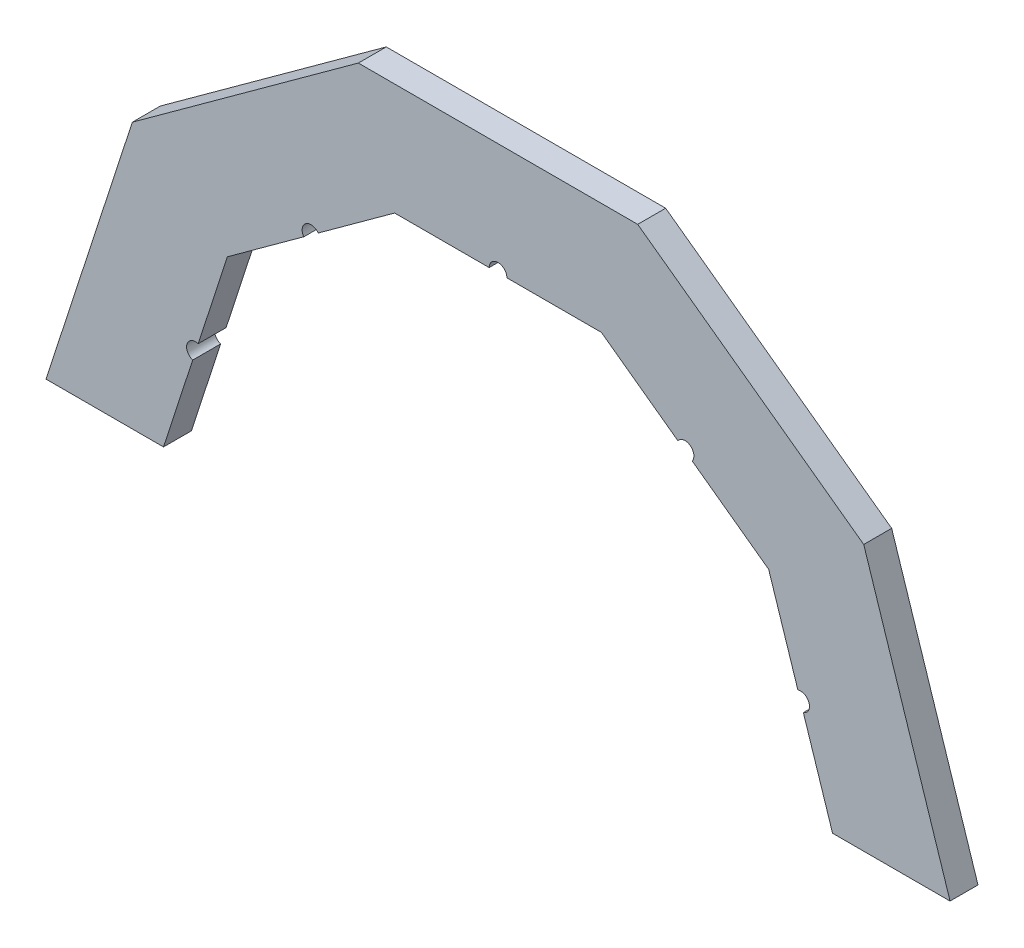
SolidWorks part; units mm, degrees
ref_plane "Front Plane" through (0, 0, 0) normal (0, 0, 1) x (1, 0, 0)
ref_plane "Top Plane" through (0, 0, 0) normal (0, 1, 0) x (1, 0, 0)
ref_plane "Right Plane" through (0, 0, 0) normal (1, 0, 0) x (0, 0, -1)
sketch "Sketch1" plane through (0, 0, 0) normal (0, 0, 1) x (1, 0, 0)
  line L0 (-96.8757, 70.3843) -> (-107.3292, 38.2118)
  line L1 (161.8034, 0) -> (130.9017, 95.1057)
  line L2 (130.9017, 95.1057) -> (50, 153.8842)
  line L3 (50, 153.8842) -> (-50, 153.8842)
  line L4 (-50, 153.8842) -> (-130.9017, 95.1057)
  line L5 (-130.9017, 95.1057) -> (-161.8034, 0)
  line L16 (119.7449, 0) -> (109.2914, 32.1725)
  line L17 (96.8757, 70.3843) -> (69.5081, 90.268)
  line L18 (37.0032, 113.8842) -> (3.175, 113.8842)
  line L19 (-37.0032, 113.8842) -> (-64.3708, 94.0005)
  line L20 (-161.8034, 0) -> (-119.7449, 0)
  line L21 (119.7449, 0) -> (161.8034, 0)
  line L22 (-161.8034, 0) -> (-130.9017, -95.1057) construction
  line L23 (-119.7449, 0) -> (-96.8757, -70.3843) construction
  line L24 (-96.8757, -70.3843) -> (-37.0032, -113.8842) construction
  line L25 (-130.9017, -95.1057) -> (-50, -153.8842) construction
  line L26 (-146.3525, -47.5528) -> (-130.9017, -95.1057) [skipped]
  line L27 (-37.0032, -113.8842) -> (37.0032, -113.8842) construction
  line L28 (37.0032, -113.8842) -> (96.8757, -70.3843) construction
  line L29 (96.8757, -70.3843) -> (119.7449, 0) construction
  line L30 (130.9017, -95.1057) -> (161.8034, 0) construction
  line L31 (130.9017, -95.1057) -> (146.3525, -47.5528) [skipped]
  line L32 (50, -153.8842) -> (130.9017, -95.1057) construction
  line L33 (-90.4508, -124.4949) -> (-50, -153.8842) [skipped]
  line L34 (-50, -153.8842) -> (50, -153.8842) construction
  line L35 (50, -153.8842) -> (90.4508, -124.4949) [skipped]
  line L36 (-50, -153.8842) -> (0, -153.8842) [skipped]
  line L37 (-109.2914, 32.1725) -> (-119.7449, 0)
  line L38 (-96.8757, 70.3843) -> (-119.7449, 0) construction
  line L39 (-69.5081, 90.268) -> (-96.8757, 70.3843)
  line L40 (-37.0032, 113.8842) -> (-96.8757, 70.3843) construction
  line L41 (-3.175, 113.8842) -> (-37.0032, 113.8842)
  line L42 (37.0032, 113.8842) -> (-37.0032, 113.8842) construction
  line L43 (64.3708, 94.0005) -> (37.0032, 113.8842)
  line L44 (96.8757, 70.3843) -> (37.0032, 113.8842) construction
  line L45 (107.3292, 38.2118) -> (96.8757, 70.3843)
  line L46 (119.7449, 0) -> (96.8757, 70.3843) construction
  arc A1 (107.3292, 38.2118) -> (109.2914, 32.1725) centre (108.3103, 35.1921) cw
  arc A2 (64.3708, 94.0005) -> (69.5081, 90.268) centre (66.9394, 92.1342) cw
  arc A3 (-3.175, 113.8842) -> (3.175, 113.8842) centre (0, 113.8842) cw
  arc A4 (-69.5081, 90.268) -> (-64.3708, 94.0005) centre (-66.9394, 92.1342) cw
  arc A5 (-109.2914, 32.1725) -> (-107.3292, 38.2118) centre (-108.3103, 35.1921) cw
  arc A6 (153.8842, 0) -> (-153.8842, 0) centre (0, 0) ccw construction
  dimension "D4" = 3.175
  dimension "D1" = 100
  dimension "D3" = 40
extrude "Boss-Extrude1" add sketch "Sketch1" along normal blind 10
